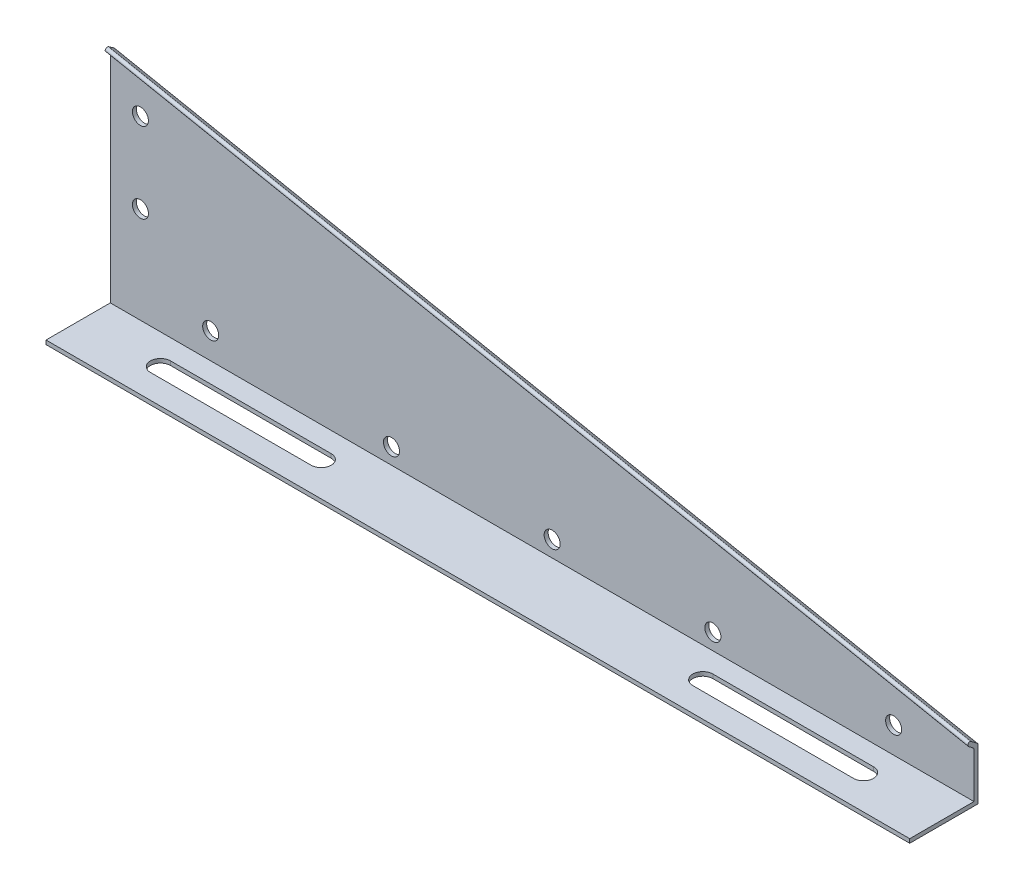
SolidWorks part; units mm, degrees
ref_plane "Front Plane" through (0, 0, 0) normal (0, 0, 1) x (1, 0, 0)
ref_plane "Top Plane" through (0, 0, 0) normal (0, 1, 0) x (1, 0, 0)
ref_plane "Right Plane" through (0, 0, 0) normal (1, 0, 0) x (0, 0, -1)
sketch "Sketch2" plane through (0, 0, 0) normal (0, 0, 1) x (1, 0, 0)
  line L0 (0, 0) -> (430, 0)
  line L1 (430, 0) -> (430, 25)
  line L2 (430, 25) -> (0, 110)
  line L3 (0, 110) -> (0, 0)
  dimension "D1" = 430
  dimension "D2" = 110
  dimension "D3" = 25
extrude "Boss-Extrude1" add sketch "Sketch2" along normal blind 2
sketch "Sketch3" plane through (0, 0, 0) normal (0, 0, -1) x (-1, 0, 0)
  line L0 (0, 110) -> (0, 0) construction
  line L1 (-430, 0) -> (0, 0)
  line L2 (-430, 0) -> (-430, 2)
  line L3 (-430, 2) -> (0, 2)
  line L4 (0, 0) -> (0, 2)
  dimension "D1" = 2
extrude "Boss-Extrude2" add sketch "Sketch3" along normal blind 30
sketch "Sketch4" plane through (0, 2, 0) normal (0, 1, 0) x (1, 0, 0)
  line L0 (215, 30) -> (215, 156.0852) construction
  line L1 (0, 30) -> (430, 30) construction
  line L2 (40, 15) -> (120, 15) construction
  line L3 (40, 20) -> (120, 20)
  line L4 (40, 10) -> (120, 10)
  line L5 (0, 30) -> (0, 0) construction
  line L6 (390, 15) -> (310, 15) construction
  line L7 (390, 20) -> (310, 20)
  line L8 (390, 10) -> (310, 10)
  arc A0 (40, 20) -> (40, 10) centre (40, 15) ccw
  arc A1 (120, 10) -> (120, 20) centre (120, 15) ccw
  arc A2 (390, 20) -> (390, 10) centre (390, 15) cw
  arc A3 (310, 10) -> (310, 20) centre (310, 15) cw
  point P6 (80, 15)
  point P16 (350, 15)
  dimension "D2" = 5
  dimension "D1" = 40
  dimension "D3" = 80
  dimension "D4" = 10
extrude "Cut-Extrude1" cut sketch "Sketch4" against normal blind 50
fillet "Fillet1" [suppressed] radius 10
sketch "Sketch7" plane through (0, 0, 2) normal (0, 0, 1) x (1, 0, 0)
  line L0 (0, 0) -> (430, 0) construction
  line L1 (0, 110) -> (0, 0) construction
  line L2 (430, 0) -> (430, 25) construction
  circle A0 centre (15, 50) radius 4
  circle A1 centre (50, 15) radius 4
  circle A2 centre (390, 15) radius 4
  circle A3 centre (15, 90) radius 4
  dimension "D3" = 8
  dimension "D4" = 8
  dimension "D5" = 8
  dimension "D10" = 8
  dimension "D1" = 50
  dimension "D2" = 15
  dimension "D6" = 15
  dimension "D7" = 50
  dimension "D8" = 15
  dimension "D9" = 40
  dimension "D11" = 90
extrude "Cut-Extrude2" cut sketch "Sketch7" against normal through all
sketch "Sketch8" plane through (0, 0, 2) normal (0, 0, 1) x (1, 0, 0)
  line L0 (140, 10) -> (220, 10) construction
  line L1 (0, 0) -> (430, 0) construction
  circle A0 centre (140, 10) radius 4
  circle A1 centre (220, 10) radius 4
  circle A2 centre (300, 10) radius 4
  circle A8 centre (50, 15) radius 4 construction
  dimension "D1" = 8
  dimension "D5" = 90
  dimension "D3" = 80
  dimension "D4" = 10
  dimension "D2" = 3
extrude "Cut-Extrude3" cut sketch "Sketch8" against normal through all
ref_plane "Plane1" through (20.9265, 105.8634, 0) normal (0.1939, 0.981, 0) x (0.981, -0.1939, 0)
ref_plane "Plane2" through (-20.9265, 4.1366, 0) normal (0.981, -0.1939, 0) x (0, 0, -1)
sketch "Sketch12" plane through (-20.9265, 4.1366, 0) normal (0.981, -0.1939, 0) x (0, 0, -1)
  line L1 (2.6685, 109.9132) -> (0, 107.9119)
  line L2 (-2, 107.9119) -> (0, 107.9119)
  line L3 (-2, 107.9119) -> (-2, 108.9119)
  line L4 (-2, 108.9119) -> (1.4685, 111.5132)
  arc A0 (1.4685, 111.5132) -> (2.6685, 109.9132) centre (2.0685, 110.7132) cw
  dimension "D1" = 2
  dimension "D3" = 1
  dimension "D2" = 5
  dimension "D4" = 1
extrude "Boss-Extrude4" add sketch "Sketch12" along normal up to surface (438.3207 mm away)
fillet "Fillet3" radius 1 2 edges at (215, 67.5, 0) (215.097, 68.5002, 2)
sketch "Sketch13" plane through (0, 0, 0) normal (-1, 0, 0) x (0, 0, 1)
  line L0 (-15, 2) -> (-15, 27.3589) construction
  line L1 (-30, 2) -> (0, 2) construction
ref_plane "Plane3" through (0, 0, -15) normal (0, 0, -1) x (-1, 0, 0)
mirror "Mirror1" about plane through (0, 0, -15) normal (0, 0, -1) of "Boss-Extrude1"
mirror "Mirror2" about plane through (0, 0, -15) normal (0, 0, -1) of "Boss-Extrude4"
fillet "Fillet4" radius 1 2 edges at (215, 67.5, -30) (215.097, 68.5002, -32)
sketch "Sketch14" plane through (0, 0, 0) normal (-1, 0, 0) x (0, 0, 1)
  line L0 (-30, 2) -> (0, 2) construction
  line L1 (-5.845, 2) -> (8.3532, 2)
  line L2 (-5.845, 2) -> (-5.845, 142.6794)
  line L3 (-5.845, 142.6794) -> (8.3532, 142.6794)
  line L4 (8.3532, 2) -> (8.3532, 142.6794)
extrude "Cut-Extrude6" cut sketch "Sketch14" against normal through all
mirror "Mirror3" about plane through (0, 0, -15) normal (0, 0, -1) of "Cut-Extrude3", "Cut-Extrude2"
